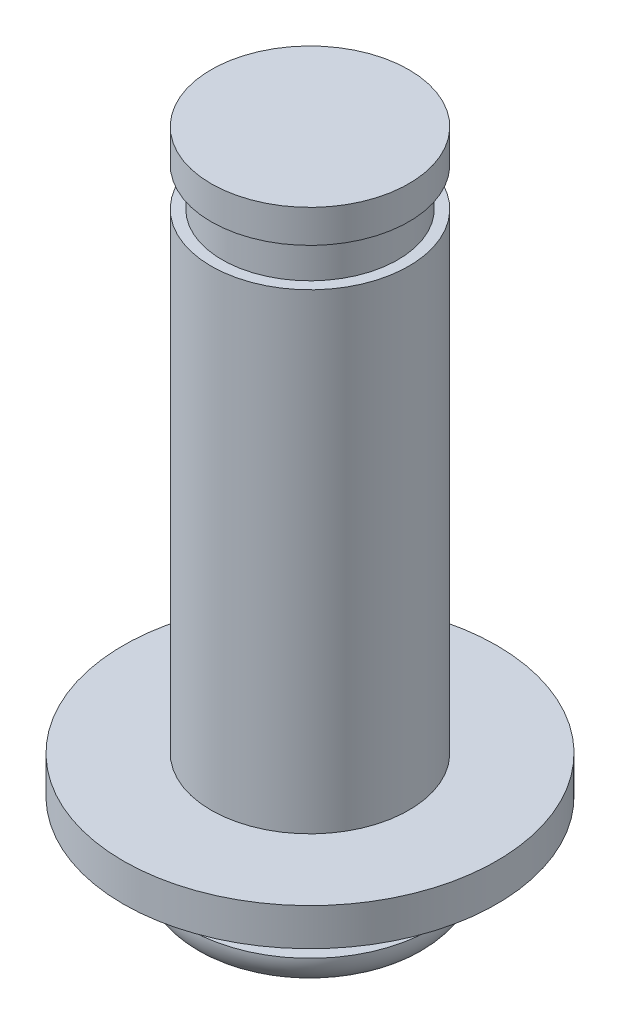
SolidWorks part; units mm, degrees
material "ASTM A36"
ref_plane "Plano frontal" through (0, 0, 0) normal (0, 0, 1) x (1, 0, 0)
ref_plane "Plano superior" through (0, 0, 0) normal (0, 1, 0) x (1, 0, 0)
ref_plane "Plano direito" through (0, 0, 0) normal (1, 0, 0) x (0, 0, -1)
sketch "Esboço1" plane through (0, 0, 0) normal (1, 0, 0) x (0, 0, -1)
  line L0 (0, 30.4) -> (0, 0)
  line L1 (0, 0) -> (-4, 0)
  line L2 (-5.5, 1.5) -> (-4.5, 1.5)
  line L3 (-4.5, 1.5) -> (-4.5, 4)
  line L4 (-4.5, 4) -> (-8.5, 4)
  line L5 (-8.5, 4) -> (-8.5, 5.7)
  line L6 (-8.5, 5.7) -> (-4.5, 5.7)
  line L7 (-4.5, 5.7) -> (-4.5, 27.15)
  line L8 (-4.5, 27.15) -> (-4, 27.15)
  line L9 (-4, 27.15) -> (-4, 28.9)
  line L10 (-4, 28.9) -> (-4.5, 28.9)
  line L11 (-4.5, 28.9) -> (-4.5, 30.4)
  line L12 (-4.5, 30.4) -> (0, 30.4)
  line L13 (0, 0) -> (0, 9633.2569) construction
  arc A0 (-4, 0) -> (-5.5, 1.5) centre (-4, 1.5) cw
  dimension "D1" = 11
  dimension "D2" = 1.5
  dimension "D3" = 17
  dimension "D4" = 9
  dimension "D5" = 1.7
  dimension "D6" = 30.4
  dimension "D7" = 2.5
  dimension "D8" = 9
  dimension "D9" = 8
  dimension "D10" = 1.5
  dimension "D11" = 1.75
revolve "Revolução1" add sketch "Esboço1" angle 360 about L13
